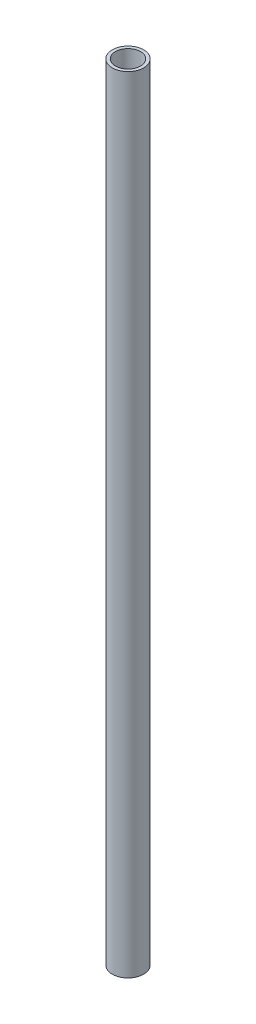
SolidWorks part; units mm, degrees
material "Thornel Mat VMA"
ref_plane "Front Plane" through (0, 0, 0) normal (0, 0, 1) x (1, 0, 0)
ref_plane "Top Plane" through (0, 0, 0) normal (0, 1, 0) x (1, 0, 0)
ref_plane "Right Plane" through (0, 0, 0) normal (1, 0, 0) x (0, 0, -1)
sketch "Sketch1" plane through (0, 0, 0) normal (0, 1, 0) x (1, 0, 0)
  circle A0 centre (0, 0) radius 5
  circle A1 centre (0, 0) radius 4
  dimension "D1" = 10
  dimension "D2" = 8
extrude "Boss-Extrude1" add sketch "Sketch1" along normal mid plane 250
